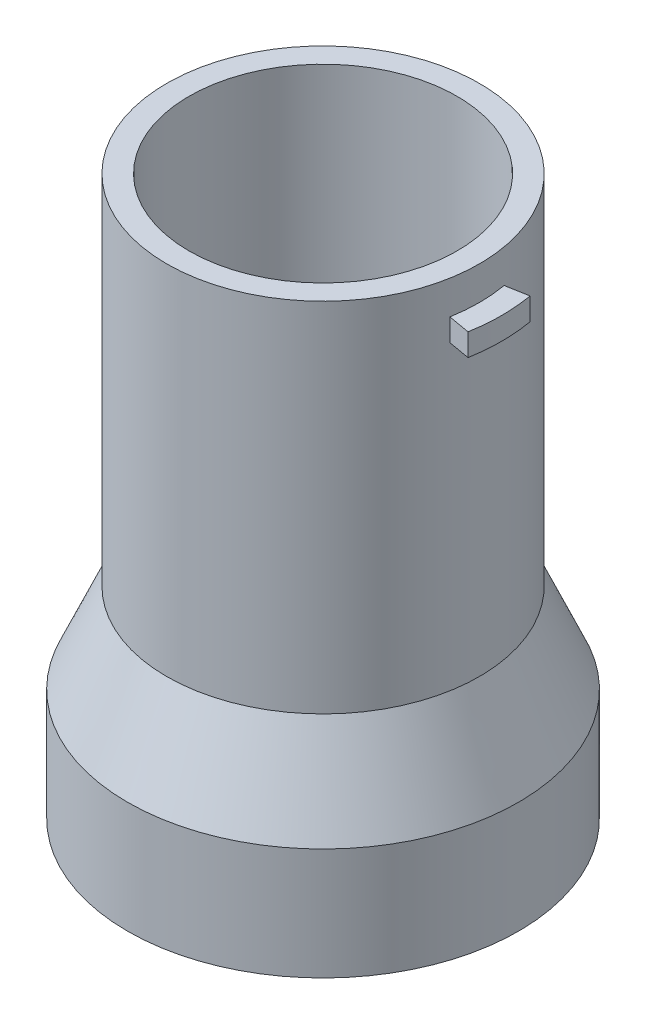
SolidWorks part; units mm, degrees
ref_plane "Front Plane" through (0, 0, 0) normal (0, 0, 1) x (1, 0, 0)
ref_plane "Top Plane" through (0, 0, 0) normal (0, 1, 0) x (1, 0, 0)
ref_plane "Right Plane" through (0, 0, 0) normal (1, 0, 0) x (0, 0, -1)
sketch "Sketch1" plane through (0, 0, 0) normal (0, 0, 1) x (1, 0, 0)
  line L0 (0, 40.4677) -> (0, -47.133) construction
  line L1 (12, 25) -> (12, -15)
  line L2 (14.5, -25) -> (17.5, -25)
  line L3 (17.5, -25) -> (17.5, -15)
  line L4 (17.5, -15) -> (14, -7)
  line L5 (14, -7) -> (14, 25)
  line L6 (14, 25) -> (12, 25)
  line L7 (12, -15) -> (14.5, -15)
  line L8 (14.5, -15) -> (14.5, -25)
  line L9 (-38.6492, 0) -> (68.272, 0) construction
  dimension "D1" = 3
  dimension "D2" = 0.5
  dimension "D3" = 12
  dimension "D4" = 2
  dimension "D5" = 10
  dimension "D6" = 8
  dimension "D7" = 40
revolve "Revolve1" add sketch "Sketch1" angle 360 about L0
ref_axis "Axis1" through (0, -42.0041, 0) along (0, 1, 0)
sketch "Sketch2" plane through (0, 0, 0) normal (0, 0, 1) x (1, 0, 0)
  line L0 (14, 22) -> (16, 22)
  line L1 (14, -7) -> (14, 25) construction
  line L2 (16, 22) -> (16, 20)
  line L3 (16, 20) -> (14, 20)
  line L4 (14, 20) -> (14, 22)
  line L5 (-14, 22) -> (-14, 20)
  line L6 (-14, 25) -> (-14, -7) construction
  line L7 (-14, 20) -> (-16, 20)
  line L8 (-16, 20) -> (-16, 22)
  line L9 (-16, 22) -> (-14, 22)
  line L10 (0, 45.3067) -> (0, -45.5409) construction
  line L11 (14, 25) -> (-14, 25) construction
  dimension "D1" = 2
  dimension "D3" = 2
  dimension "D4" = 3
revolve "Revolve2" add sketch "Sketch2" angle 20 mid plane about L10
sketch "Sketch3" plane through (0, 0, 0) normal (0, 0, 1) x (1, 0, 0)
  line L1 (-16.7, -18.2) -> (-14.5, -18.2)
  line L2 (-16.7, -18.2) -> (-16.7, -25)
  line L3 (-16.7, -25) -> (-14.5, -25)
  line L4 (-14.5, -18.2) -> (-14.5, -25)
  line L5 (-17.5, -25) -> (17.5, -25) construction
  line L6 (-17.5, -15) -> (-17.5, -25) construction
  line L7 (16.7, -25) -> (14.5, -25)
  line L8 (16.7, -25) -> (16.7, -18.2)
  line L9 (16.7, -18.2) -> (14.5, -18.2)
  line L10 (14.5, -25) -> (14.5, -18.2)
  line L14 (0, -11.0207) -> (0, -43.2503) construction
  line L15 (-14.5, -15) -> (14.5, -15) construction
  dimension "D2" = 3.2
  dimension "D3" = 0.8
revolve "Cut-Revolve1" cut sketch "Sketch3" angle 25 mid plane about L14
sketch "Sketch4" plane through (0, 0, 0) normal (0, 0, 1) x (1, 0, 0)
  line L1 (-16.7, -18.2) -> (-16.7, -20.7)
  line L2 (-16.7, -18.2) -> (-16.7, -25) construction
  line L3 (-16.7, -20.7) -> (-12, -20.7)
  line L4 (16.7, -25) -> (16.7, -18.2) construction
  line L6 (16.7, -20.7) -> (16.7, -18.2)
  line L7 (16.7, -18.2) -> (12, -18.2)
  line L8 (-12, -20.7) -> (-12, -18.2)
  line L9 (12, -18.2) -> (12, -20.7)
  line L10 (12, -20.7) -> (16.7, -20.7)
  line L11 (-12, -18.2) -> (-16.7, -18.2)
  dimension "D1" = 2.5
revolve "Cut-Revolve2" cut sketch "Sketch4" angle 45 about axis through (0, -42.0041, 0) along (0, 1, 0)
